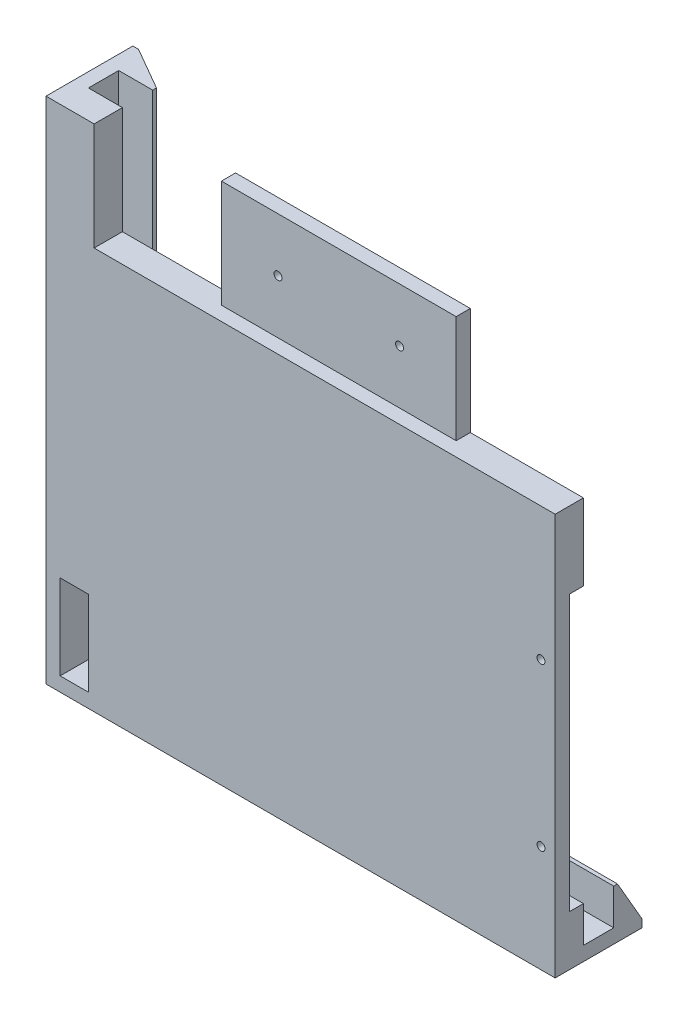
SolidWorks part; units mm, degrees
ref_plane "Alzado" through (0, 0, 0) normal (0, 0, 1) x (1, 0, 0)
ref_plane "Planta" through (0, 0, 0) normal (0, 1, 0) x (1, 0, 0)
ref_plane "Vista lateral" through (0, 0, 0) normal (1, 0, 0) x (0, 0, -1)
sketch "Croquis1" plane through (0, 0, 0) normal (0, 0, 1) x (1, 0, 0)
  line L1 (0, 0) -> (180, 0)
  line L2 (0, 0) -> (0, 180)
  line L3 (0, 180) -> (180, 180)
  line L4 (180, 0) -> (180, 180)
  dimension "D1" = 180
extrude "Saliente-Extruir1" add sketch "Croquis1" along normal blind 30.7
sketch "Croquis2" plane through (0, 0, 0) normal (0, 0, -1) x (-1, 0, 0)
  line L0 (-180, 0) -> (-180, 180) construction
  line L1 (-180, 17.79) -> (-17.01, 17.79)
  line L2 (-180, 17.79) -> (-180, 180)
  line L3 (-180, 180) -> (-17.01, 180)
  line L4 (-17.01, 17.79) -> (-17.01, 180)
  line L5 (-180, 180) -> (0, 180) construction
  line L6 (0, 180) -> (0, 0) construction
  line L7 (0, 0) -> (-180, 0) construction
  dimension "D1" = 17.01
  dimension "D2" = 17.79
extrude "Cortar-Extruir1" cut sketch "Croquis2" against normal blind 20.7
sketch "Croquis4" plane through (0, 180, 0) normal (0, 1, 0) x (1, 0, 0)
  line L0 (17.01, -20.7) -> (17.01, 0) construction
  line L1 (180, -20.7) -> (5, -20.7)
  line L2 (180, -20.7) -> (180, -10)
  line L3 (180, -10) -> (5, -10)
  line L4 (5, -20.7) -> (5, -10)
  dimension "D1" = 10.7
  dimension "D2" = 12.01
extrude "Cortar-Extruir2" cut sketch "Croquis4" against normal offset from surface (175 mm away) 5 up to face at (90, 0, 15.35)
sketch "Croquis5" plane through (0, 0, 20.7) normal (0, 0, -1) x (-1, 0, 0)
  line L1 (-140, 142) -> (-180, 142)
  line L2 (-140, 142) -> (-140, 180)
  line L3 (-140, 180) -> (-180, 180)
  line L4 (-180, 142) -> (-180, 180)
  line L5 (-57.01, 142) -> (-17.01, 142)
  line L6 (-57.01, 142) -> (-57.01, 180)
  line L7 (-57.01, 180) -> (-17.01, 180)
  line L8 (-17.01, 142) -> (-17.01, 180)
extrude "Cortar-Extruir3" cut sketch "Croquis5" against normal blind 10
sketch "Croquis6" plane through (0, 0, 30.7) normal (0, 0, 1) x (1, 0, 0)
  line L0 (140, 142) -> (140, 180) construction
  line L1 (57.01, 180) -> (140, 180)
  line L2 (57.01, 180) -> (57.01, 142)
  line L3 (57.01, 142) -> (140, 142)
  line L4 (140, 180) -> (140, 142)
  line L5 (180, 142) -> (140, 142) construction
extrude "Cortar-Extruir4" cut sketch "Croquis6" against normal blind 5
sketch "Croquis7" plane through (0, 0, 20.7) normal (0, 0, -1) x (-1, 0, 0)
  line L1 (-170, 115) -> (-180, 115)
  line L2 (-170, 115) -> (-170, 17.79)
  line L3 (-170, 17.79) -> (-180, 17.79)
  line L4 (-180, 115) -> (-180, 17.79)
extrude "Cortar-Extruir5" cut sketch "Croquis7" against normal blind 5
sketch "Croquis8" plane through (0, 0, 20.7) normal (0, 0, -1) x (-1, 0, 0)
  line L1 (-5, 5) -> (-15, 5)
  line L2 (-5, 5) -> (-5, 35)
  line L3 (-5, 35) -> (-15, 35)
  line L4 (-15, 5) -> (-15, 35)
  dimension "D1" = 30
  dimension "D2" = 10
extrude "Cortar-Extruir6" cut sketch "Croquis8" against normal blind 20
sketch "Croquis9" plane through (0, 0, 20.7) normal (0, 0, -1) x (-1, 0, 0)
  line L0 (-140, 142) -> (-140, 180) construction
  line L1 (-57.01, 180) -> (-57.01, 142) construction
  line L2 (-170, 115) -> (-180, 115) construction
  line L3 (-180, 17.79) -> (-17.01, 17.79) construction
  circle A0 centre (-120, 161) radius 1.4
  circle A1 centre (-77.01, 161) radius 1.4
  circle A2 centre (-175, 95) radius 1.4
  circle A3 centre (-175, 37.79) radius 1.4
  point P10 (0, 0)
  point P11 (-140, 161)
  point P14 (0, 0)
  point P17 (-175, 115)
  dimension "D1" = 2.8
  dimension "D2" = 20
  dimension "D3" = 20
  dimension "D4" = 20
  dimension "D5" = 20
extrude "Cortar-Extruir7" cut sketch "Croquis9" against normal blind 20
chamfer "Chaflán1" distance 15 angle 30 2 edges at (98.505, 17.79, 0) (17.01, 98.895, 0)
